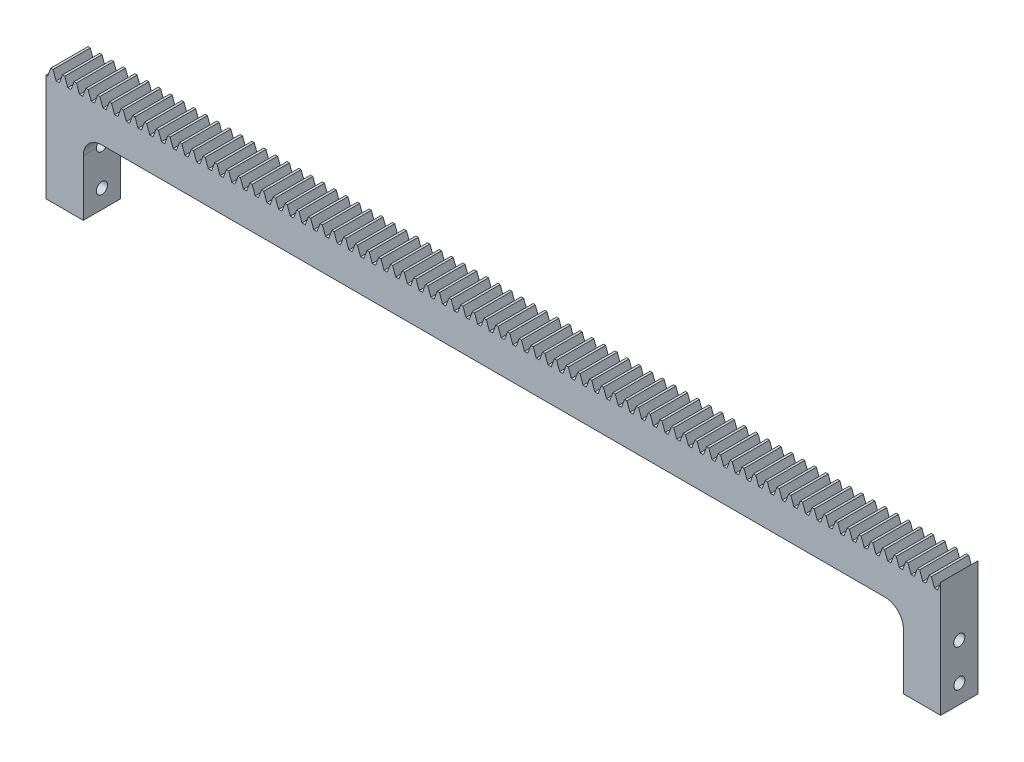
SolidWorks part; units mm, degrees
extrude "Blank" add sketch "BlankSke" against normal blind 10
sketch "BlankSke" plane through (0, 0, 0) normal (0, 0, 1) x (1, 0, 0)
  line L1 (0, 0) -> (240, 0)
  line L2 (0, 0) -> (0, 11)
  line L3 (0, 11) -> (240, 11)
  line L4 (240, 0) -> (240, 11)
  dimension "Length" = 240
  dimension "Blank_height" = 11
material "ABS PC"
ref_plane "Plane1" through (0, 0, 0) normal (0, 0, 1) x (1, 0, 0)
ref_plane "Plane2" through (0, 0, 0) normal (0, 1, 0) x (1, 0, 0)
ref_plane "Plane3" through (0, 0, 0) normal (1, 0, 0) x (0, 0, -1)
sketch "HoldingSke" plane through (0, 0, 0) normal (0, 1, 0) x (1, 0, 0)
  line L0 (0, 0) -> (0.1392, 0.9903)
  line L1 (-15, 0) -> (100, 0) construction
  line L2 (0, 0) -> (-2.1039, 2.3779)
  line L3 (0, 0) -> (-11.863, 4.5341)
  line L4 (0, 0) -> (1.7955, 8.4473)
  line L5 (0, 0) -> (-23.7986, -8.8762)
  line L6 (0, 0) -> (-10.5278, -7.1032)
  line L9 (-71.009, 38.7566) -> (154.5173, 120.8414)
  line L10 (-76.2, 3.3779) -> (-66.2, 3.3779)
  line L11 (0, 0) -> (-10, 0)
  line L12 (-76.2, 101.6) -> (-76.162, 101.6)
  line L13 (24.9733, 27.94) -> (52.9518, 28.4284)
  line L14 (24.9733, 27.94) -> (24.9743, 27.94)
  line L15 (24.9733, 27.94) -> (100.4006, 29.5858)
  circle A0 centre (0, 0) radius 19.05
  circle A1 centre (0, 0) radius 5
  circle A2 centre (0, 0) radius 12.7
  dimension "MPH" = 10
  dimension "Diameter" = 38.1
  dimension "Num_teeth" = 78
  dimension "Pitch" = 1
  dimension "Show_teeth" = 998
  dimension "Thickness" = 12.7
  dimension "Ap" = 20
  dimension "Pitch_height" = 10
  dimension "Width" = 10
  dimension "Backlash" = 0.038
  dimension "Addendum_fac" = 1
  dimension "Dedendum_fac" = 1.25
  dimension "Clearance_fac" = 0.25
  dimension "Dedendum_add" = 0.001
  dimension "Length" = 240
  dimension "Module" = 1
sketch "TooCutSkeIll" plane through (0, 0, 0) normal (0, 0, 1) x (1, 0, 0)
  line L0 (-1.2538, 10.9737) -> (-0.5045, 8.9152)
  line L1 (-0.2687, 8.75) -> (0.2687, 8.75)
  line L2 (0.5045, 8.9152) -> (1.2538, 10.9737)
  line L3 (240, 11) -> (0, 11) construction
  line L4 (0, 0) -> (0, 64.897) construction
  line L5 (-13.208, 10) -> (12.954, 10) construction
  line L6 (0, 0) -> (240, 0) construction
  line L7 (0.8994, 10) -> (0.8994, 48.7463) construction
  line L8 (-0.8994, 10) -> (-0.8994, 48.7463) construction
  line L9 (1.2914, 11) -> (1.2914, 11.0254)
  line L10 (-1.2914, 11) -> (-1.2914, 11.0254)
  line L11 (-1.2914, 11.0254) -> (1.2914, 11.0254)
  arc A0 (0.2687, 8.75) -> (0.5045, 8.9152) centre (0.2687, 9.001) ccw
  arc A1 (-0.5045, 8.9152) -> (-0.2687, 8.75) centre (-0.2687, 9.001) ccw
  arc A2 (1.2914, 11) -> (1.2538, 10.9737) centre (1.2914, 10.96) ccw
  arc A3 (-1.2538, 10.9737) -> (-1.2914, 11) centre (-1.2914, 10.96) ccw
  dimension "Pitch_height" = 10
  dimension "Addendum_plus" = 1.0254
  dimension "Pressure_angle" = 20
  dimension "Gap_width" = 1.7988
  dimension "Dedendum" = 1.25
extrude "ToothCutIll" [suppressed] cut sketch "TooCutSkeIll" against normal through all
sketch "TooCutSkeSim" plane through (0, 0, 0) normal (0, 0, 1) x (1, 0, 0)
  line L0 (0.4444, 8.75) -> (-0.4444, 8.75)
  line L1 (1.2726, 11.0254) -> (0.4444, 8.75)
  line L2 (0, 17.4625) -> (0, 53.467) construction
  line L3 (1.2726, 11.0254) -> (-1.2726, 11.0254)
  line L6 (-1.2726, 11.0254) -> (-0.4444, 8.75)
  line L9 (-0.8994, 10) -> (0.8994, 10) construction
  line L10 (0, 0) -> (240, 0) construction
  line L11 (0.8994, 10) -> (0.8994, 53.467) construction
  line L12 (-0.8994, 10) -> (-0.8994, 53.467) construction
  dimension "Pitch_height" = 10
  dimension "Addendum_plus" = 1.0254
  dimension "Pressure_angle" = 20
  dimension "Gap_width" = 1.7988
  dimension "Dedendum" = 1.25
extrude "ToothCutSim" cut sketch "TooCutSkeSim" against normal through all
pattern_linear "TeethCuts" count 77 spacing 3.1416 along (1, 0, 0) of "ToothCutIll", "ToothCutSim"
sketch "Sketch1" plane through (0, 0, 0) normal (0, -1, 0) x (-1, 0, 0)
  line L0 (0, 10) -> (-240, 10) construction
  line L1 (0, 0) -> (-10, 0)
  line L2 (0, 0) -> (0, 10)
  line L3 (0, 10) -> (-10, 10)
  line L4 (-10, 0) -> (-10, 10)
  line L5 (0, 0) -> (-240, 0) construction
  line L6 (-240, 10) -> (-230, 10)
  line L7 (-240, 10) -> (-240, 0)
  line L8 (-240, 0) -> (-230, 0)
  line L9 (-230, 10) -> (-230, 0)
  dimension "D1" = 10
  dimension "D2" = 10
extrude "Boss-Extrude1" add sketch "Sketch1" along normal blind 20
fillet "Fillet1" radius 5 2 edges at (10, 0, -5) (230, 0, -5)
sketch "Sketch2" plane through (240, 0, 0) normal (1, 0, 0) x (0, 0, -1)
  line L0 (10, -20) -> (0, -20) construction
  line L1 (0, -20) -> (0, 10.9329) construction
  circle A0 centre (5, -15) radius 1.5
  circle A1 centre (4.9782, -5) radius 1.5
  point P8 (0, -4.5335)
  dimension "D1" = 3
  dimension "D2" = 3
  dimension "D6" = 5
  dimension "D3" = 10
  dimension "D4" = 5
  dimension "D5" = 5
extrude "Cut-Extrude1" cut sketch "Sketch2" against normal through all
sketch "Sketch3" plane through (0, 0, -10) normal (0, 0, -1) x (-1, 0, 0)
  line L0 (-240, 9.875) -> (0, 9.875) construction
  line L3 (-15, 0) -> (-225, 0) construction
  dimension "D1" = 9.875
sketch "Sketch4" plane through (0, 0, -10) normal (0, 0, -1) x (-1, 0, 0)
  line L0 (-242.6507, 9.875) -> (0.0211, 9.875) construction
  line L3 (-15, 0) -> (-225, 0) construction
  dimension "D1" = 9.875
equation "' \"Module@HoldingSke\" = 6.35"
equation "' \"Num_teeth@HoldingSke\" = 12"
equation "' \"Ap@HoldingSke\" =  20"
equation "' \"Ap@HoldingSke\" = 20"
equation "' \"Width@HoldingSke\" = 0.25 * 25.4"
equation "' \"Show_teeth@HoldingSke\" = 500"
equation "' \"Backlash@HoldingSke\" = 0.009 * 25.4"
equation "' \"Addendum_fac@HoldingSke\" = 1.0"
equation "' \"Dedendum_fac@HoldingSke\" = 1.25"
equation "' \"Dedendum_add@HoldingSke\" = 0.00005 * 25.4"
equation "' \"Clearance_fac@HoldingSke\" = 0.25"
equation "' \"Pitch_height@HoldingSke\" = 1 * 25.4"
equation "' \"Length@HoldingSke\" = 4.71 * 25.4"
equation "\"Pitch@HoldingSke\" = 1 / \"Module@HoldingSke\""
equation "\"MPH@HoldingSke\" = \"Dedendum_fac@HoldingSke\" / \"Pitch@HoldingSke\" + 2 * \"Dedendum_add@HoldingSke\" + 0.002 * 25.4"
equation "\"MPH@HoldingSke\" = ((sgn( \"MPH@HoldingSke\" - \"Pitch_height@HoldingSke\")+1)*( \"MPH@HoldingSke\" - \"Pitch_height@HoldingSke\"))/2 + \"Pitch_height@HoldingSke\""
equation "\"Blank_height@BlankSke\" = \"Pitch_height@HoldingSke\" + \"Addendum_fac@HoldingSke\"  / \"Pitch@HoldingSke\" "
equation "\"Length@BlankSke\" =  \"Length@HoldingSke\""
equation "\"Face_width@Blank\" = \"Width@HoldingSke\""
equation "\"Pressure_angle@TooCutSkeIll\" = \"Ap@HoldingSke\""
equation "\"Addendum_plus@TooCutSkeIll\" =  \"Addendum_fac@HoldingSke\"  / \"Pitch@HoldingSke\" + 0.001 *25.4"
equation "\"Dedendum@TooCutSkeIll\" = \"Dedendum_fac@HoldingSke\"  / \"Pitch@HoldingSke\""
equation "\"Pitch_height@TooCutSkeIll\" =  \"MPH@HoldingSke\""
equation "\"Gap_width@TooCutSkeIll\" = 3.14159265 / 2 / \"Pitch@HoldingSke\" + 6 * \"Backlash@HoldingSke\""
equation "\"Pressure_angle@TooCutSkeSim\" = \"Ap@HoldingSke\""
equation "\"Addendum_plus@TooCutSkeSim\" =  \"Addendum_fac@HoldingSke\"  / \"Pitch@HoldingSke\" + 0.001 * 25.4"
equation "\"Dedendum@TooCutSkeSim\" = \"Dedendum_fac@HoldingSke\"  / \"Pitch@HoldingSke\""
equation "\"Pitch_height@TooCutSkeSim\" =  \"MPH@HoldingSke\""
equation "\"Gap_width@TooCutSkeSim\" = 3.14159265 / 2 / \"Pitch@HoldingSke\" + 6 * \"Backlash@HoldingSke\""
equation "\"Root_fillet@TooCutSkeIll\" = \"Clearance_fac@HoldingSke\" / \"Pitch@HoldingSke\" + \"Dedendum_add@HoldingSke\""
equation "\"Break_rad@TooCutSkeIll\" = 0.02 / \"Pitch@HoldingSke\" * 2"
equation "\"Linear_pitch@TeethCuts\" = 3.14159265 / \"Pitch@HoldingSke\""
equation "\"Num_teeth@HoldingSke\" = int( ( \"Length@HoldingSke\" + 0 ) / (3.14159265 / \"Pitch@HoldingSke\")) + 0.9999  + 1"
equation " \"Num_teeth@TeethCuts\" = int( \"Show_teeth@HoldingSke\" ) + 1"
equation " \"Num_teeth@TeethCuts\" = ((sgn( \"Num_teeth@TeethCuts\" - \"Num_teeth@HoldingSke\" )-1)*( \"Num_teeth@TeethCuts\" - \"Num_teeth@HoldingSke\" ))/-2+ \"Num_teeth@HoldingSke\""
equation " \"Num_teeth@TeethCuts\" = ((sgn( \"Num_teeth@TeethCuts\" - 2.0)+1)*( \"Num_teeth@TeethCuts\" - 2.0))/2 +2.0"
